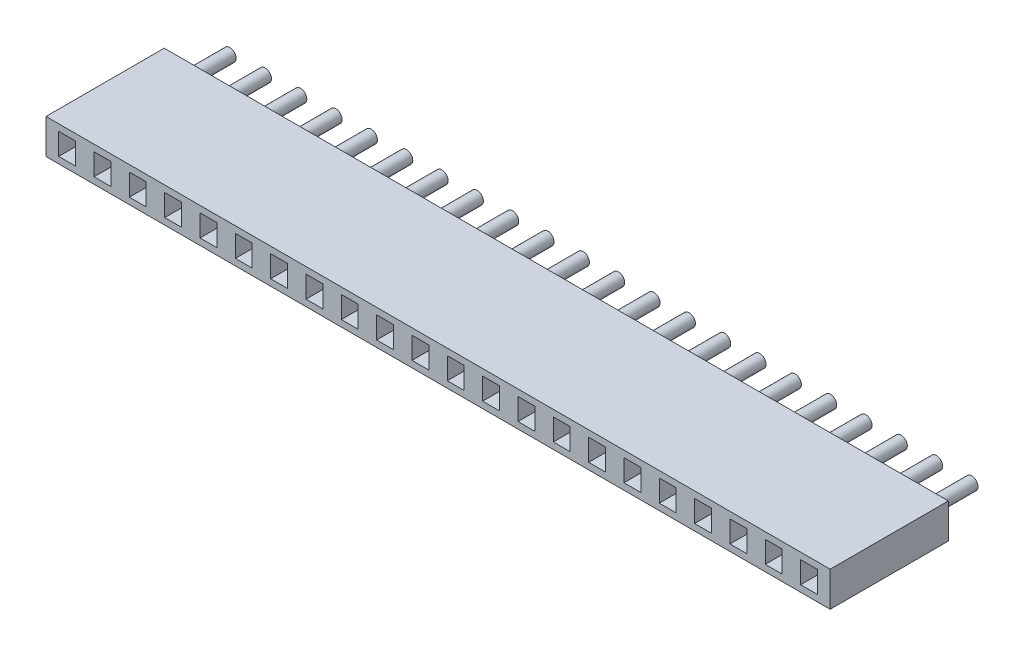
SolidWorks part; units mm, degrees
ref_plane "前视基准面" through (0, 0, 0) normal (0, 0, 1) x (1, 0, 0)
ref_plane "上视基准面" through (0, 0, 0) normal (0, 1, 0) x (1, 0, 0)
ref_plane "右视基准面" through (0, 0, 0) normal (1, 0, 0) x (0, 0, -1)
sketch "草图1" plane through (0, 0, 0) normal (0, 0, 1) x (1, 0, 0)
  line L1 (0, 0) -> (56.38, 0)
  line L2 (0, 0) -> (0, 2.5)
  line L3 (0, 2.5) -> (56.38, 2.5)
  line L4 (56.38, 0) -> (56.38, 2.5)
  dimension "D1" = 56.38
  dimension "D2" = 2.5
extrude "凸台-拉伸1" add sketch "草图1" along normal blind 8.5
sketch "草图2" plane through (0, 0, 8.5) normal (0, 0, 1) x (1, 0, 0)
  line L0 (28.19, 2.5) -> (28.19, 18.7346) construction
  line L1 (56.38, 2.5) -> (0, 2.5) construction
  line L2 (0, 1.25) -> (60.5126, 1.25) construction
  line L3 (0, 2.5) -> (0, 0) construction
  line L5 (26.3147, 2.0316) -> (27.5253, 2.0316)
  line L6 (26.3147, 2.0316) -> (26.3147, 0.4684)
  line L7 (26.3147, 0.4684) -> (27.5253, 0.4684)
  line L8 (27.5253, 2.0316) -> (27.5253, 0.4684)
  line L9 (26.3147, 2.0316) -> (27.5253, 0.4684) construction
  line L10 (26.3147, 0.4684) -> (27.5253, 2.0316) construction
  point P8 (26.92, 1.25)
  dimension "D1" = 1.27
extrude "切除-拉伸1" cut sketch "草图2" against normal blind 5
pattern_linear "阵列(线性)1" count 12 spacing 2.54 along (1, 0, 0) of "切除-拉伸1"
pattern_linear "阵列(线性)2" count 11 spacing 2.54 along (-1, 0, 0) of "切除-拉伸1"
sketch "草图3" plane through (0, 0, 0) normal (0, 0, -1) x (-1, 0, 0)
  line L2 (0, 1.25) -> (-62.9534, 1.25) construction
  line L3 (0, 2.5) -> (0, 0) construction
  line L4 (-54.86, 2.0316) -> (-54.86, 0.4684) construction
  line L5 (-55.4653, 2.0316) -> (-54.2547, 2.0316) construction
  line L6 (-54.2547, 0.4684) -> (-55.4653, 0.4684) construction
  circle A0 centre (-54.86, 1.25) radius 0.45
  dimension "D1" = 0.9
extrude "凸台-拉伸2" add sketch "草图3" along normal blind 3.2
pattern_linear "阵列(线性)3" count 22 spacing 2.54 along (-1, 0, 0) of "凸台-拉伸2"
